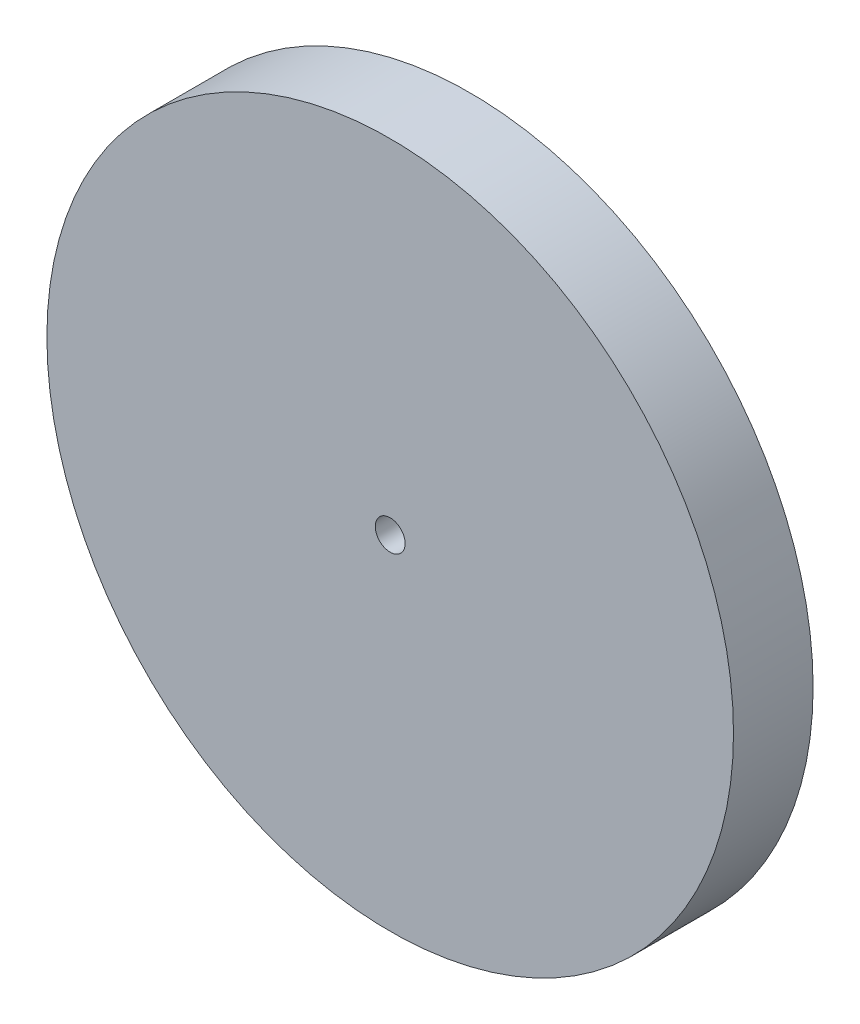
SolidWorks part; units mm, degrees
ref_plane "Front Plane" through (0, 0, 0) normal (0, 0, 1) x (1, 0, 0)
ref_plane "Top Plane" through (0, 0, 0) normal (0, 1, 0) x (1, 0, 0)
ref_plane "Right Plane" through (0, 0, 0) normal (1, 0, 0) x (0, 0, -1)
sketch "Sketch2" plane through (0, 0, 0) normal (0, 0, 1) x (1, 0, 0)
  circle A0 centre (0, 0) radius 34.5
  circle A1 centre (0, 0) radius 1.5
  dimension "D1" = 69
  dimension "D2" = 3
extrude "Boss-Extrude1" add sketch "Sketch2" along normal blind 8
